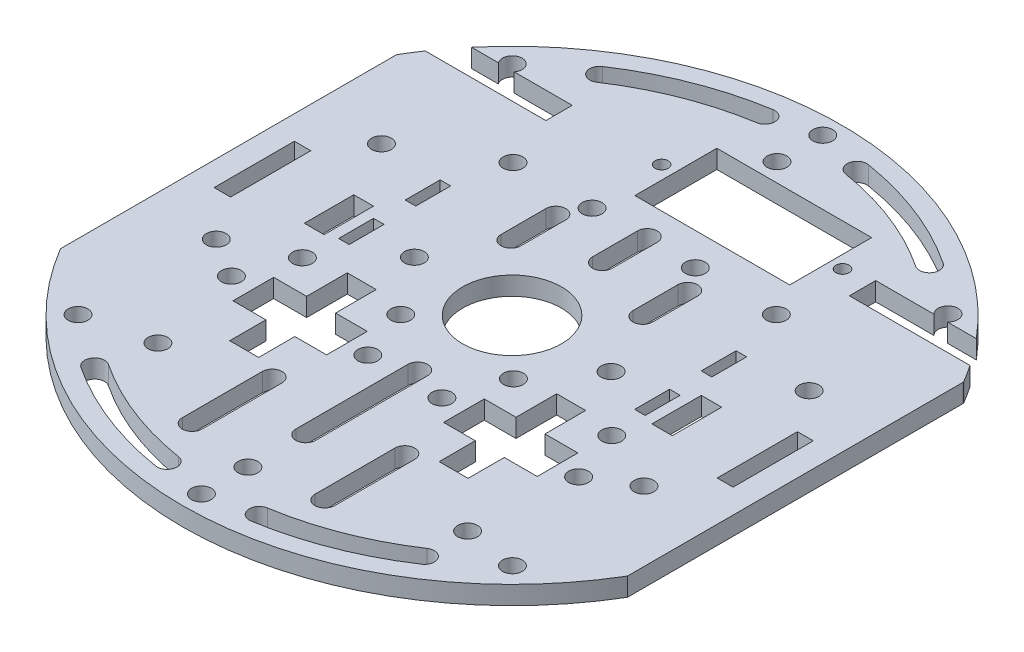
SolidWorks part; units mm, degrees
ref_plane "Plan de face" through (0, 0, 0) normal (0, 0, 1) x (1, 0, 0)
ref_plane "Plan de dessus" through (0, 0, 0) normal (0, 1, 0) x (1, 0, 0)
ref_plane "Plan de droite" through (0, 0, 0) normal (1, 0, 0) x (0, 0, -1)
sketch "Esquisse1" plane through (0, 0, 0) normal (0, 1, 0) x (1, 0, 0)
  line L0 (230, 494) -> (1150, 494) construction
  line L1 (230, 494) -> (1150, 494) construction
  line L2 (1049.7748, 1753.5) -> (2703.7748, 1753.5) construction
  line L3 (35.8344, 116.4831) -> (35.8344, 167.52)
  line L4 (121.9144, 167.4519) -> (121.9144, 116.5513)
  line L5 (88.9323, 158.6153) -> (88.9323, 151.8005) construction
  line L6 (121.9144, 116.5513) -> (121.9144, 116.4831)
  line L7 (55.7773, 128.9032) -> (60.7773, 128.9032)
  line L8 (55.7773, 128.9032) -> (55.7773, 122.7236)
  line L9 (55.7773, 122.7236) -> (60.7773, 122.7236)
  line L10 (60.7773, 122.7236) -> (60.7773, 117.2265)
  line L11 (60.7773, 117.2265) -> (65.1744, 117.2265)
  line L12 (65.1744, 117.2265) -> (65.1744, 122.7236)
  line L13 (65.1744, 122.7236) -> (69.9925, 122.7236)
  line L14 (69.9925, 122.7236) -> (69.9925, 128.9032)
  line L15 (69.9925, 128.9032) -> (65.1744, 128.9032)
  line L16 (65.1744, 128.9032) -> (65.1744, 135.081)
  line L17 (65.1744, 135.081) -> (60.7773, 135.081)
  line L18 (60.7773, 135.081) -> (60.7773, 128.9032)
  line L19 (68.9056, 158.6153) -> (68.9056, 151.8005) construction
  line L20 (70.4056, 158.6153) -> (70.4056, 151.8005)
  line L21 (67.4056, 158.6153) -> (67.4056, 151.8005)
  line L22 (78.7942, 162.6149) -> (78.7942, 155.8001) construction
  line L23 (80.2942, 162.6149) -> (80.2942, 155.8001)
  line L24 (77.2942, 162.6149) -> (77.2942, 155.8001)
  line L25 (68.7987, 115.6611) -> (68.7987, 103.5071) construction
  line L26 (70.2987, 115.6611) -> (70.2987, 103.5071)
  line L27 (67.2987, 115.6611) -> (67.2987, 103.5071)
  line L28 (39.458, 148.3706) -> (41.958, 148.3706)
  line L29 (41.958, 148.3706) -> (41.958, 136.1826)
  line L30 (41.958, 136.1826) -> (39.458, 136.1826)
  line L31 (39.458, 136.1826) -> (39.458, 148.3706)
  line L32 (55.6035, 149.0513) -> (57.2035, 149.0513)
  line L33 (54.0029, 138.3405) -> (51.0029, 138.3405)
  line L34 (54.0029, 138.3405) -> (54.0029, 145.8405)
  line L35 (54.0029, 145.8405) -> (51.0029, 145.8405)
  line L36 (51.0029, 138.3405) -> (51.0029, 145.8405)
  line L37 (55.6035, 138.9387) -> (57.2035, 138.9387)
  line L38 (55.6035, 138.9387) -> (55.6035, 144.2387)
  line L39 (55.6035, 144.2387) -> (57.2035, 144.2387)
  line L40 (57.2035, 138.9387) -> (57.2035, 144.2387)
  line L41 (55.6035, 149.0513) -> (55.6035, 154.3513)
  line L42 (55.6035, 154.3513) -> (57.2035, 154.3513)
  line L43 (57.2035, 149.0513) -> (57.2035, 154.3513)
  line L44 (35.8344, 142.0016) -> (121.9144, 142.0016) construction
  line L45 (78.8744, 142.0016) -> (78.8744, 76.4199) construction
  line L46 (78.9075, 127.6391) -> (78.9075, 110.6391) construction
  line L47 (80.4075, 127.6391) -> (80.4075, 110.6391)
  line L48 (77.4075, 127.6391) -> (77.4075, 110.6391)
  line L49 (35.8344, 162.6149) -> (121.9144, 162.6149) construction
  line L50 (87.4323, 158.6153) -> (87.4323, 151.8005)
  line L51 (90.4323, 158.6153) -> (90.4323, 151.8005)
  line L52 (88.9323, 115.6611) -> (88.9323, 103.5071) construction
  line L53 (87.4323, 115.6611) -> (87.4323, 103.5071)
  line L54 (90.4323, 115.6611) -> (90.4323, 103.5071)
  line L55 (100.5453, 149.0513) -> (100.5453, 154.3513)
  line L56 (102.1454, 154.3551) -> (100.5453, 154.3513)
  line L57 (102.1454, 149.0551) -> (102.1454, 154.3551)
  line L58 (100.5454, 138.9387) -> (100.5454, 144.2387)
  line L59 (102.1454, 144.2387) -> (100.5454, 144.2387)
  line L60 (102.1454, 138.9387) -> (102.1454, 144.2387)
  line L61 (102.1454, 138.9387) -> (100.5454, 138.9387)
  line L62 (106.8661, 138.3405) -> (106.8661, 145.8405)
  line L63 (103.7673, 145.8405) -> (106.8661, 145.8405)
  line L64 (103.7673, 138.3405) -> (103.7673, 145.8405)
  line L65 (103.7673, 138.3405) -> (106.8661, 138.3405)
  line L66 (102.1454, 149.0551) -> (100.5453, 149.0513)
  line L67 (118.245, 136.1826) -> (118.245, 148.3706)
  line L68 (115.8366, 136.1826) -> (118.245, 136.1826)
  line L69 (115.8366, 148.3706) -> (115.8366, 136.1826)
  line L70 (118.245, 148.3706) -> (115.8366, 148.3706)
  line L71 (96.9716, 135.081) -> (96.9716, 128.9032)
  line L72 (92.5745, 135.081) -> (96.9716, 135.081)
  line L73 (92.5745, 128.9032) -> (92.5745, 135.081)
  line L74 (87.7564, 128.9032) -> (92.5745, 128.9032)
  line L75 (87.7564, 122.7236) -> (87.7564, 128.9032)
  line L76 (92.5745, 122.7236) -> (87.7564, 122.7236)
  line L77 (92.5745, 117.2265) -> (92.5745, 122.7236)
  line L78 (96.9716, 117.2265) -> (92.5745, 117.2265)
  line L79 (96.9716, 122.7236) -> (96.9716, 117.2265)
  line L80 (101.9716, 122.7236) -> (96.9716, 122.7236)
  line L81 (101.9716, 128.9032) -> (101.9716, 122.7236)
  line L82 (101.9716, 128.9032) -> (96.9716, 128.9032)
  line L84 (72.4514, 167.0754) -> (95.9525, 167.0754)
  line L85 (72.4514, 167.0754) -> (72.4514, 179.5181)
  line L86 (72.4514, 179.5181) -> (95.9525, 179.5181)
  line L87 (95.9525, 167.0754) -> (95.9525, 179.5181)
  arc A1 (35.8344, 116.4831) -> (121.9144, 116.4831) centre (78.8744, 142.0016) ccw
  circle A2 centre (78.8744, 142.0016) radius 7.5
  arc A3 (121.8796, 167.5788) -> (35.8344, 167.52) centre (78.8744, 142.0016) ccw
  circle A4 centre (55.6386, 111.4684) radius 1.5
  circle A5 centre (52.4216, 125.8435) radius 1.5
  circle A6 centre (46.4093, 129.5605) radius 1.5
  circle A7 centre (45.8266, 109.1504) radius 1.5
  circle A9 centre (55.394, 133.6521) radius 1.5
  circle A10 centre (63.822, 142.2216) radius 1.5
  circle A11 centre (70.318, 133.6521) radius 1.5
  circle A12 centre (73.1582, 125.8134) radius 1.5
  circle A14 centre (78.7794, 94.9342) radius 1.5
  circle A15 centre (58.8593, 162.1633) radius 1.5
  circle A16 centre (78.7794, 101.9917) radius 1.5
  circle A17 centre (45.8266, 175.0806) radius 1.5
  circle A18 centre (78.7794, 182.3243) radius 1.5
  circle A19 centre (46.4093, 154.6416) radius 1.5
  circle A20 centre (78.7794, 189.2658) radius 1.5
  circle A21 centre (70.8644, 162.1633) radius 1.5
  arc A24 (70.4056, 158.6153) -> (67.4056, 158.6153) centre (68.9056, 158.6153) ccw
  arc A25 (67.4056, 151.8005) -> (70.4056, 151.8005) centre (68.9056, 151.8005) ccw
  arc A26 (80.2942, 162.6149) -> (77.2942, 162.6149) centre (78.7942, 162.6149) ccw
  arc A27 (77.2942, 155.8001) -> (80.2942, 155.8001) centre (78.7942, 155.8001) ccw
  arc A30 (70.2987, 115.6611) -> (67.2987, 115.6611) centre (68.7987, 115.6611) ccw
  arc A31 (67.2987, 103.5071) -> (70.2987, 103.5071) centre (68.7987, 103.5071) ccw
  arc A35 (53.8408, 103.6654) -> (71.8854, 96.6187) centre (79.1758, 141.9141) ccw construction
  arc A36 (53.0125, 102.4148) -> (71.647, 95.1377) centre (79.1758, 141.9141) ccw
  arc A37 (54.6692, 104.9159) -> (72.1238, 98.0996) centre (79.1758, 141.9141) ccw
  arc A38 (54.6692, 104.9159) -> (53.0125, 102.4148) centre (53.8408, 103.6654) ccw
  arc A39 (71.647, 95.1377) -> (72.1238, 98.0996) centre (71.8854, 96.6187) ccw
  circle A40 centre (78.9075, 110.6391) radius 1.5
  circle A41 centre (78.9075, 127.6391) radius 1.5
  arc A42 (80.4075, 127.6391) -> (77.4075, 127.6391) centre (78.9075, 127.6391) ccw
  arc A43 (77.4075, 110.6391) -> (80.4075, 110.6391) centre (78.9075, 110.6391) ccw
  arc A44 (53.8408, 180.3378) -> (71.8854, 187.3845) centre (79.1758, 142.0891) cw construction
  arc A45 (53.0125, 181.5883) -> (71.647, 188.8654) centre (79.1758, 142.0891) cw
  arc A46 (54.6692, 179.0872) -> (72.1238, 185.9035) centre (79.1758, 142.0891) cw
  arc A47 (54.6692, 179.0872) -> (53.0125, 181.5883) centre (53.8408, 180.3378) cw
  arc A48 (71.647, 188.8654) -> (72.1238, 185.9035) centre (71.8854, 187.3845) cw
  circle A49 centre (70.4056, 173.1853) radius 1
  arc A50 (87.4323, 158.6153) -> (90.4323, 158.6153) centre (88.9323, 158.6153) cw
  arc A51 (90.4323, 151.8005) -> (87.4323, 151.8005) centre (88.9323, 151.8005) cw
  arc A52 (87.4323, 115.6611) -> (90.4323, 115.6611) centre (88.9323, 115.6611) cw
  arc A53 (90.4323, 103.5071) -> (87.4323, 103.5071) centre (88.9323, 103.5071) cw
  arc A54 (103.908, 103.6654) -> (85.8635, 96.6187) centre (78.573, 141.9141) cw construction
  arc A55 (104.7364, 102.4148) -> (86.1018, 95.1377) centre (78.573, 141.9141) cw
  arc A56 (103.0797, 104.9159) -> (85.6251, 98.0996) centre (78.573, 141.9141) cw
  arc A57 (103.0797, 104.9159) -> (104.7364, 102.4148) centre (103.908, 103.6654) cw
  arc A58 (86.1018, 95.1377) -> (85.6251, 98.0996) centre (85.8635, 96.6187) cw
  arc A59 (103.908, 180.3378) -> (85.8635, 187.3845) centre (78.573, 142.0891) ccw construction
  arc A60 (104.7364, 181.5883) -> (86.1018, 188.8654) centre (78.573, 142.0891) ccw
  arc A61 (103.0797, 179.0872) -> (85.6251, 185.9035) centre (78.573, 142.0891) ccw
  arc A62 (103.0797, 179.0872) -> (104.7364, 181.5883) centre (103.908, 180.3378) ccw
  arc A63 (86.1018, 188.8654) -> (85.6251, 185.9035) centre (85.8635, 187.3845) ccw
  circle A64 centre (97.8643, 173.1853) radius 1
  circle A66 centre (86.5331, 162.1633) radius 1.5
  circle A67 centre (111.3396, 154.6416) radius 1.5
  circle A68 centre (111.7891, 175.2768) radius 1.5
  circle A69 centre (98.8379, 162.1633) radius 1.5
  circle A70 centre (84.4104, 125.8134) radius 1.5
  circle A71 centre (87.3272, 133.7572) radius 1.5
  circle A72 centre (93.7831, 142.1236) radius 1.5
  circle A73 centre (102.2561, 133.7572) radius 1.5
  circle A74 centre (105.1676, 125.8134) radius 1.5
  circle A75 centre (111.8296, 109.1035) radius 1.5
  circle A76 centre (111.3396, 129.5605) radius 1.5
  circle A78 centre (103.8661, 110.2588) radius 1.5
  arc A79 (121.8796, 167.5788) -> (121.9144, 167.4519) centre (121.6662, 167.4519) cw
  point P32 (68.9056, 155.2079)
  point P38 (55.6386, 111.4684)
  point P42 (78.7942, 159.2075)
  point P63 (68.7987, 109.5841)
  point P106 (78.9075, 119.1391)
  point P110 (62.487, 99.1788)
  point P129 (62.487, 184.8244)
  point P138 (35.8344, 167.52)
  point P139 (88.9323, 155.2079)
  point P146 (88.9323, 109.5841)
  point P154 (95.2619, 99.1788)
  point P162 (95.2619, 184.8244)
  point P225 (121.9144, 167.52)
  point P226 (102.1103, 111.4684)
  dimension "D3" = 15
  dimension "D5" = 3
  dimension "D6" = 1.5
  dimension "D7" = 1.5
  dimension "D14" = 3
  dimension "D17" = 2
  dimension "D18" = 3
  dimension "D19" = 3
  dimension "D20" = 3
  dimension "D21" = 3
  dimension "D22" = 3
  dimension "D23" = 3
  dimension "D24" = 3
  dimension "D25" = 3
  dimension "D26" = 3
  dimension "D27" = 3
  dimension "D29" = 3
  dimension "D33" = 1.5
  dimension "D35" = 3
  dimension "D2" = 51.0369
  dimension "D4" = 5
  dimension "D8" = 2.5
  dimension "D9" = 12.1879
  dimension "D10" = 3
  dimension "D11" = 7.5
  dimension "D12" = 1.6
  dimension "D13" = 5.3
  dimension "D15" = 3
  dimension "D16" = 17
  dimension "D28" = 12.1541
  dimension "D30" = 6.8148
  dimension "D31" = 43.04
  dimension "D32" = 43.04
  dimension "D34" = 6.8148
  dimension "D36" = 12.1541
  dimension "D37" = 1.6
  dimension "D38" = 5.3
extrude "Boss.-Extru.1" add sketch "Esquisse1" along normal blind 2.8 contours A79 A3 L3 A1 L6 L4 A76 A74 A72 A70 A68 A66 A55 A58 A56 A57 L54 A53 L53 A52 L51 A51 L50 A50 A45 A48 A46 A47 L57 L66 L55 L56 L60 L61 L58 L59 L33 L36
sketch "Esquisse2" plane through (0, 0, 0) normal (0, -1, 0) x (-1, 0, 0)
  line L0 (-121.9144, 167.4519) -> (-121.9144, 116.4831) construction
  line L1 (-101.9144, 174.1788) -> (-120.2144, 174.1788)
  line L2 (-101.9144, 174.1788) -> (-101.9144, 170.1788)
  line L3 (-101.9144, 170.1788) -> (-120.2144, 170.1788)
  line L4 (-120.2144, 174.1788) -> (-120.2144, 170.1788)
  line L5 (-35.8344, 116.4831) -> (-35.8344, 167.52) construction
  line L6 (-37.5344, 174.1788) -> (-55.8344, 174.1788)
  line L7 (-37.5344, 174.1788) -> (-37.5344, 170.1788)
  line L8 (-37.5344, 170.1788) -> (-55.8344, 170.1788)
  line L9 (-55.8344, 174.1788) -> (-55.8344, 170.1788)
  dimension "D1" = 1.7
  dimension "D2" = 4
  dimension "D3" = 18.3
  dimension "D5" = 1.7
  dimension "D6" = 6.6
  dimension "D8" = 18.3
extrude "Enlèv. mat.-Extru.1" cut sketch "Esquisse2" against normal blind 10
